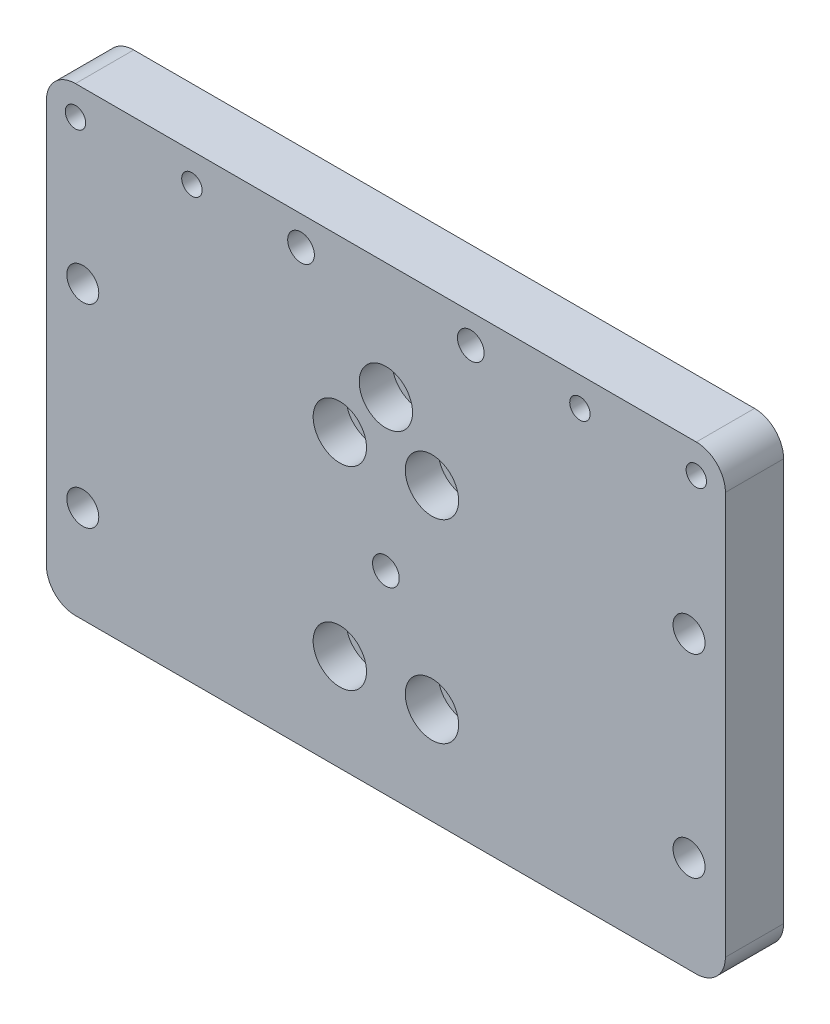
SolidWorks part; units mm, degrees
material "1060 Alloy"
ref_plane "Front Plane" through (0, 0, 0) normal (0, 0, 1) x (1, 0, 0)
ref_plane "Top Plane" through (0, 0, 0) normal (0, 1, 0) x (1, 0, 0)
ref_plane "Right Plane" through (0, 0, 0) normal (1, 0, 0) x (0, 0, -1)
sketch "Sketch1" plane through (0, 0, 0) normal (0, 0, 1) x (1, 0, 0)
  line L1 (70, -47.5) -> (-70, -47.5)
  line L2 (70, -47.5) -> (70, 47.5)
  line L3 (70, 47.5) -> (-70, 47.5)
  line L4 (-70, -47.5) -> (-70, 47.5)
  line L5 (70, -47.5) -> (-70, 47.5) construction
  line L6 (70, 47.5) -> (-70, -47.5) construction
  point P0 (0, 0)
  dimension "D1" = 140
  dimension "D2" = 95
extrude "Boss-Extrude1" add sketch "Sketch1" along normal mid plane 12
sketch "Sketch2" plane through (0, 0, 6) normal (0, 0, 1) x (1, 0, 0)
  line L0 (0, 74.5662) -> (0, 4.4431) construction
  line L1 (-70, -47.5) -> (70, -47.5) construction
  line L2 (-9.5, 12.5) -> (-9.5, -27.5) construction
  line L3 (70, 47.5) -> (-70, 47.5) construction
  line L4 (-64, 41.5) -> (-40, 41.5) construction
  line L5 (-40, 41.5) -> (-17.5, 41.5) construction
  line L6 (-70, 47.5) -> (-70, -47.5) construction
  line L7 (-62.5, 12.5) -> (-62.5, -27.5) construction
  circle A0 centre (0, 23.5) radius 2.75
  circle A1 centre (0, -7.5) radius 2.75
  circle A2 centre (-9.5, 12.5) radius 3.3
  circle A3 centre (-9.5, -27.5) radius 3.3
  circle A4 centre (-17.5, 41.5) radius 2.75
  circle A5 centre (-40, 41.5) radius 2.1
  circle A6 centre (-64, 41.5) radius 2.1
  circle A7 centre (-62.5, 12.5) radius 3.3
  circle A8 centre (-62.5, -27.5) radius 3.3
  circle A9 centre (62.5, -27.5) radius 3.3
  circle A10 centre (62.5, 12.5) radius 3.3
  circle A11 centre (64, 41.5) radius 2.1
  circle A12 centre (40, 41.5) radius 2.1
  circle A13 centre (17.5, 41.5) radius 2.75
  circle A14 centre (9.5, -27.5) radius 3.3
  circle A15 centre (9.5, 12.5) radius 3.3
  dimension "D1" = 6.6
  dimension "D2" = 4.2
  dimension "D3" = 5.5
  dimension "D4" = 40
  dimension "D5" = 20
  dimension "D6" = 19
  dimension "D7" = 35
  dimension "D8" = 24
  dimension "D9" = 6
  dimension "D10" = 24
  dimension "D11" = 22.5
  dimension "D12" = 6
  dimension "D13" = 7.5
  dimension "D14" = 20
  dimension "D15" = 40
extrude "Cut-Extrude1" cut sketch "Sketch2" against normal through all
sketch "Sketch3" plane through (0, 0, 6) normal (0, 0, 1) x (1, 0, 0)
  circle A0 centre (-9.5, -27.5) radius 5.5
  circle A1 centre (9.5, -27.5) radius 5.5
  circle A2 centre (9.5, 12.5) radius 5.5
  circle A3 centre (0, 23.5) radius 5.5
  circle A4 centre (-9.5, 12.5) radius 5.5
  dimension "D1" = 11
extrude "Cut-Extrude2" cut sketch "Sketch3" against normal blind 6.8
fillet "Fillet1" radius 6 4 edges at (70, -47.5, 0) (70, 47.5, 0) (-70, -47.5, 0) (-70, 47.5, 0)
equation "\"M5_tap\"=4.2mm\t\t\t\t\t\t\t' Below you can do mesurements as follows: cm, mm, ft, in, m, "
equation "\"M5_clearence\"=5.5mm"
equation "\"M6_tap\"=5mm"
equation "\"M6_clearence\"=6.6mm"
equation "\"D1@Sketch2\"=\"M6_clearence\""
equation "\"D2@Sketch2\"=\"M5_tap\""
equation "\"D3@Sketch2\"=\"M5_clearence\""
